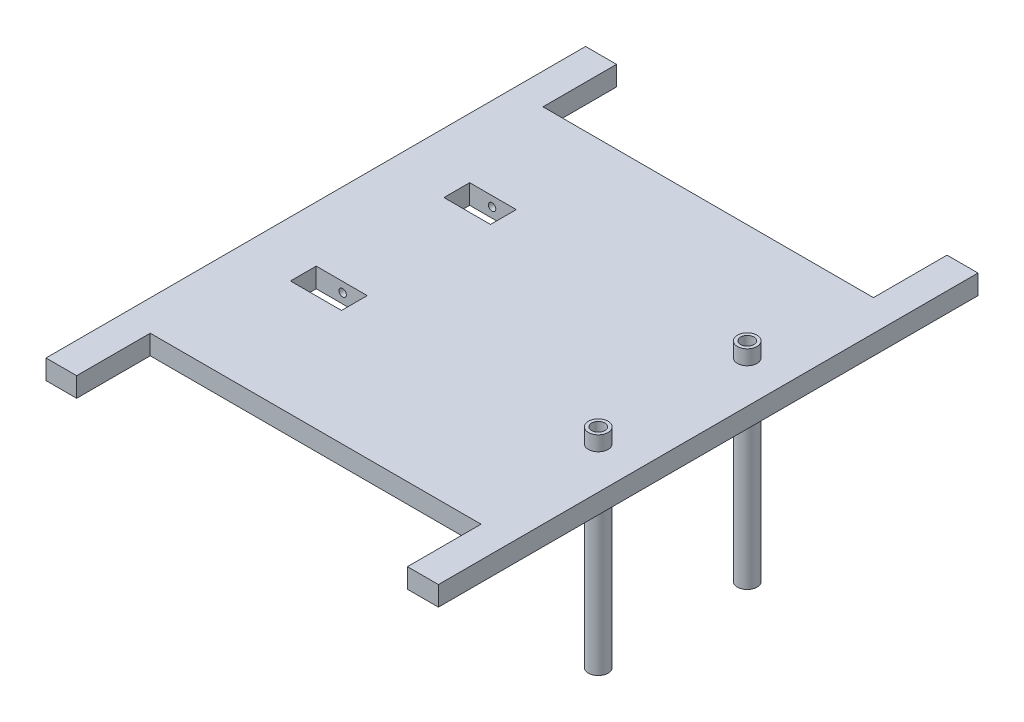
SolidWorks part; units mm, degrees
ref_plane "Front Plane" through (0, 0, 0) normal (0, 0, 1) x (1, 0, 0)
ref_plane "Top Plane" through (0, 0, 0) normal (0, 1, 0) x (1, 0, 0)
ref_plane "Right Plane" through (0, 0, 0) normal (1, 0, 0) x (0, 0, -1)
sketch "Sketch1" plane through (0, 0, 0) normal (1, 0, 0) x (0, 0, -1)
  line L1 (-80, -4) -> (80, -4)
  line L2 (-80, -4) -> (-80, 4)
  line L3 (-80, 4) -> (80, 4)
  line L4 (80, -4) -> (80, 4)
  line L5 (-80, -4) -> (80, 4) construction
  line L6 (-80, 4) -> (80, -4) construction
  point P0 (0, 0)
  dimension "D1" = 160
  dimension "D2" = 8
extrude "Boss-Extrude1" add sketch "Sketch1" along normal blind 160
sketch "Sketch2" plane through (0, 0, 80) normal (0, 0, 1) x (1, 0, 0)
  line L0 (160, -4) -> (0, -4) construction
  line L1 (0, 4) -> (12.5, 4)
  line L2 (0, 4) -> (0, -4)
  line L3 (0, -4) -> (12.5, -4)
  line L4 (12.5, 4) -> (12.5, -4)
  dimension "D1" = 12.5
extrude "Boss-Extrude2" add sketch "Sketch2" along normal blind 30
sketch "Sketch3" plane through (0, 0, 80) normal (0, 0, 1) x (1, 0, 0)
  line L0 (160, 4) -> (12.5, 4) construction
  line L1 (160, -4) -> (147.37, -4)
  line L2 (160, -4) -> (160, 4)
  line L3 (160, 4) -> (147.37, 4)
  line L4 (147.37, -4) -> (147.37, 4)
  dimension "D1" = 12.63
extrude "Boss-Extrude3" add sketch "Sketch3" along normal blind 30
sketch "Sketch4" plane through (0, 0, -80) normal (0, 0, -1) x (-1, 0, 0)
  line L0 (-160, -4) -> (0, -4) construction
  line L1 (-160, 4) -> (-147.37, 4)
  line L2 (-160, 4) -> (-160, -4)
  line L3 (-160, -4) -> (-147.37, -4)
  line L4 (-147.37, 4) -> (-147.37, -4)
  dimension "D1" = 12.63
extrude "Boss-Extrude4" add sketch "Sketch4" along normal blind 30
sketch "Sketch5" plane through (0, 0, -80) normal (0, 0, -1) x (-1, 0, 0)
  line L0 (-147.37, -4) -> (0, -4) construction
  line L1 (0, 4) -> (-12.63, 4)
  line L2 (0, 4) -> (0, -4)
  line L3 (0, -4) -> (-12.63, -4)
  line L4 (-12.63, 4) -> (-12.63, -4)
  dimension "D1" = 12.63
extrude "Boss-Extrude5" add sketch "Sketch5" along normal blind 30
sketch "Sketch6" plane through (0, 4, 0) normal (0, 1, 0) x (1, 0, 0)
  line L0 (0, 33.0158) -> (33.9683, 33.0158) construction
  line L1 (0, 110) -> (0, -110) construction
  line L2 (0, -27.7315) -> (33.0588, -27.7315) construction
  line L4 (24.4683, 38.2658) -> (43.4683, 38.2658)
  line L5 (24.4683, 38.2658) -> (24.4683, 27.7658)
  line L6 (24.4683, 27.7658) -> (43.4683, 27.7658)
  line L7 (43.4683, 38.2658) -> (43.4683, 27.7658)
  line L8 (24.4683, 38.2658) -> (43.4683, 27.7658) construction
  line L9 (24.4683, 27.7658) -> (43.4683, 38.2658) construction
  line L10 (22.6494, -32.9815) -> (43.4683, -32.9815)
  line L11 (22.6494, -32.9815) -> (22.6494, -22.4815)
  line L12 (22.6494, -22.4815) -> (43.4683, -22.4815)
  line L13 (43.4683, -32.9815) -> (43.4683, -22.4815)
  line L14 (22.6494, -32.9815) -> (43.4683, -22.4815) construction
  line L15 (22.6494, -22.4815) -> (43.4683, -32.9815) construction
  point P14 (43.4683, 33.0158)
  point P15 (22.6494, -27.7315)
  dimension "D1" = 19
  dimension "D2" = 60.7474
  dimension "D3" = 10.5
  dimension "D4" = 10.5
extrude "Cut-Extrude1" cut sketch "Sketch6" against normal blind 10
sketch "Sketch8" plane through (0, 0, -38.2658) normal (0, 0, 1) x (1, 0, 0)
  circle A0 centre (33.6192, 0) radius 1.5
extrude "Cut-Extrude4" cut sketch "Sketch8" against normal mid plane 50
sketch "Sketch9" plane through (0, 0, 22.4815) normal (0, 0, 1) x (1, 0, 0)
  circle A0 centre (33.4468, 0) radius 1.5
extrude "Cut-Extrude5" cut sketch "Sketch9" against normal mid plane 50
sketch "Sketch10" plane through (0, 0, 0) normal (0, 1, 0) x (1, 0, 0)
  line L0 (24.4683, 33.0158) -> (142.895, 33.0158) construction
  line L1 (24.4683, 38.2658) -> (24.4683, 27.7658) construction
  line L2 (22.6494, -27.7315) -> (142.895, -27.7315) construction
  line L3 (22.6494, -22.4815) -> (22.6494, -32.9815) construction
  circle A0 centre (142.895, -27.7315) radius 4
  circle A1 centre (142.895, 33.0158) radius 4
  dimension "D1" = 8
extrude "Boss-Extrude6" add sketch "Sketch10" against normal blind 85 from offset 10
sketch "Sketch13" plane through (0, 10, 0) normal (0, 1, 0) x (1, 0, 0)
  line L0 (138.895, -27.7315) -> (142.895, -27.7315) construction
  circle A0 centre (142.895, -27.7315) radius 4 construction
  circle A1 centre (142.895, -27.7315) radius 4 construction
  circle A2 centre (142.895, -27.7315) radius 2.7
  dimension "D1" = 4
extrude "Cut-Extrude6" cut sketch "Sketch13" against normal blind 85
sketch "Sketch14" plane through (0, 10, 0) normal (0, 1, 0) x (1, 0, 0)
  line L0 (138.895, 33.0158) -> (142.895, 33.0158) construction
  circle A0 centre (142.895, 33.0158) radius 4 construction
  circle A1 centre (142.895, 33.0158) radius 4 construction
  circle A2 centre (142.895, 33.0158) radius 2.7
  dimension "D1" = 4
extrude "Cut-Extrude7" cut sketch "Sketch14" against normal blind 85
